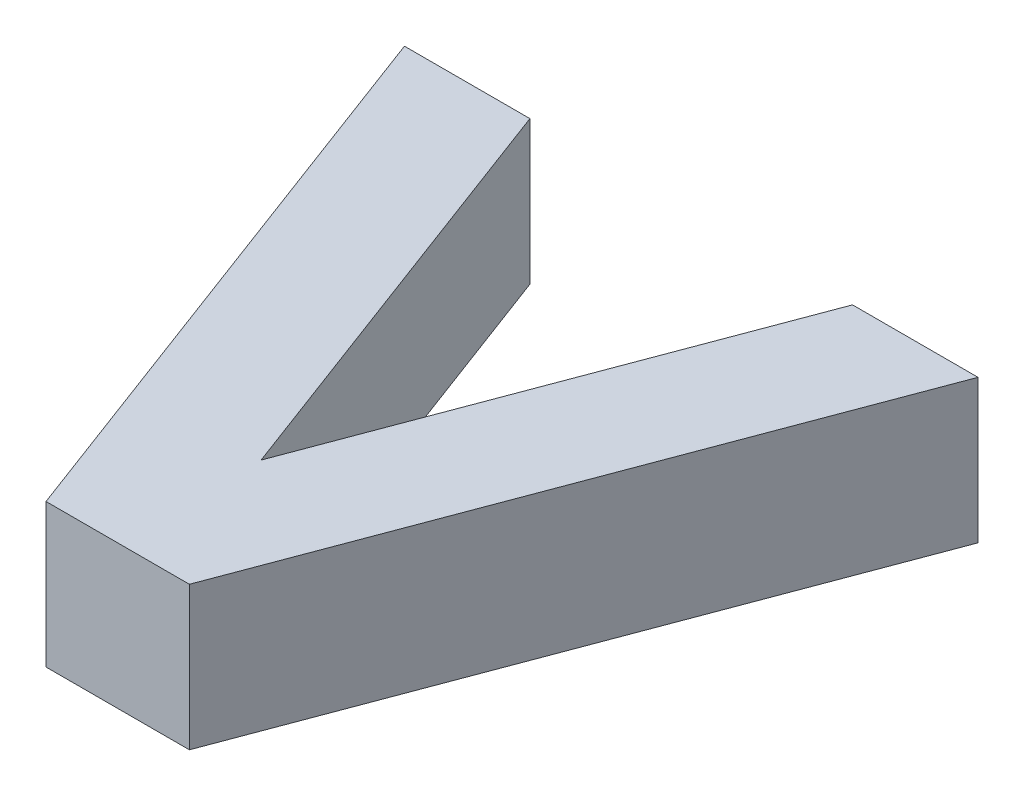
SolidWorks part; units mm, degrees
ref_plane "Front Plane" through (0, 0, 0) normal (0, 0, 1) x (1, 0, 0)
ref_plane "Top Plane" through (0, 0, 0) normal (0, 1, 0) x (1, 0, 0)
ref_plane "Right Plane" through (0, 0, 0) normal (1, 0, 0) x (0, 0, -1)
sketch "Sketch1" plane through (0, 0, 0) normal (0, 1, 0) x (1, 0, 0)
  line L0 (0, 0) -> (0, 5) construction
  line L1 (-2.5, 0) -> (2.5, 0)
  line L2 (2.5, 0) -> (10, 20)
  line L3 (10, 20) -> (5.625, 20)
  line L4 (5.625, 20) -> (0, 5)
  line L5 (-2.5, 0) -> (-10, 20)
  line L6 (-10, 20) -> (-5.625, 20)
  line L7 (-5.625, 20) -> (0, 5)
  dimension "D1" = 2.5
  dimension "D2" = 5
  dimension "D3" = 10
  dimension "D4" = 20
extrude "Boss-Extrude1" add sketch "Sketch1" along normal blind 5 contours L5 L6 L7 L4 L3 L2 L1
